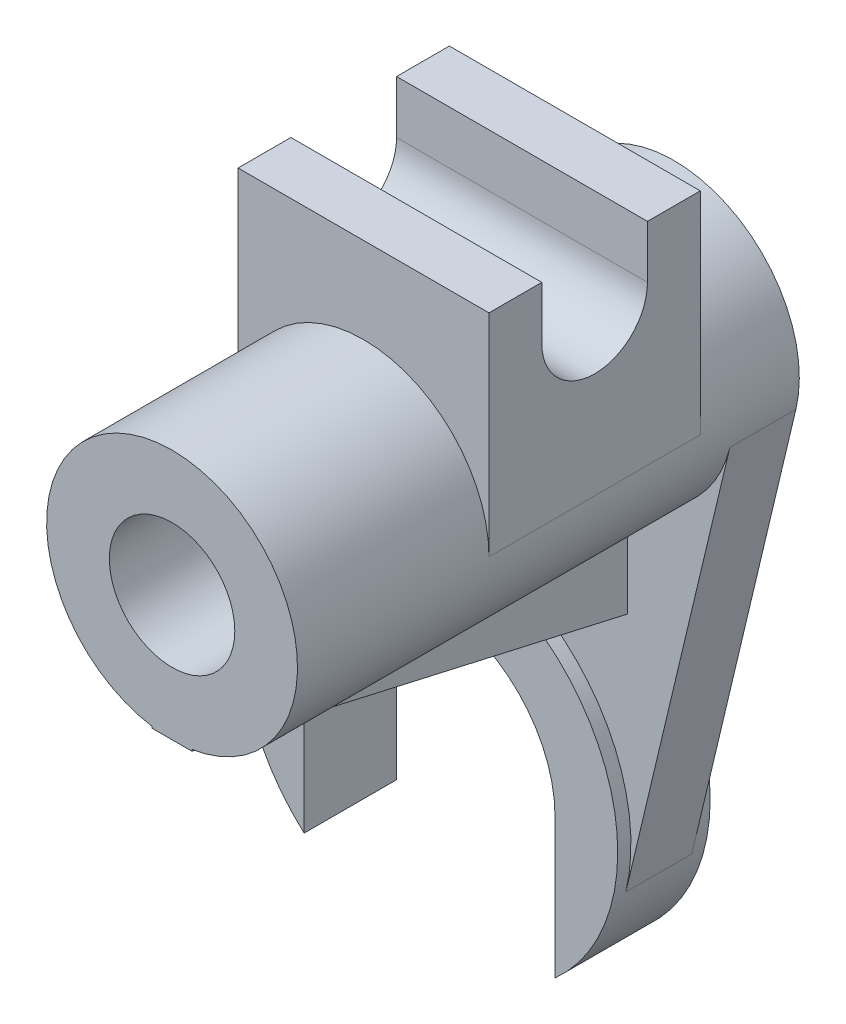
SolidWorks part; units mm, degrees
ref_plane "Front Plane" through (0, 0, 0) normal (0, 0, 1) x (1, 0, 0)
ref_plane "Top Plane" through (0, 0, 0) normal (0, 1, 0) x (1, 0, 0)
ref_plane "Right Plane" through (0, 0, 0) normal (1, 0, 0) x (0, 0, -1)
sketch "Sketch1" plane through (0, 0, 0) normal (0, 0, 1) x (1, 0, 0)
  circle A0 centre (0, 0) radius 19
  dimension "D1" = 38
extrude "Boss-Extrude1" add sketch "Sketch1" along normal mid plane 76
sketch "Sketch2" plane through (0, 0, -38) normal (0, 0, -1) x (-1, 0, 0)
  line L0 (6, -64) -> (6, -85.2426)
  line L1 (44, -64) -> (44, -85.2426)
  arc A0 (44, -64) -> (6, -64) centre (25, -64) ccw
  arc A1 (44, -85.2426) -> (6, -85.2426) centre (25, -64) ccw
  dimension "D1" = 57
  dimension "D3" = 38
  dimension "D2" = 64
  dimension "D4" = 25
extrude "Boss-Extrude2" add sketch "Sketch2" along normal blind 2 and the other way blind 12 separate body
sketch "Sketch3" plane through (0, 0, -38) normal (0, 0, -1) x (-1, 0, 0)
  line L0 (-18.4835, -4.3998) -> (-2.7253, -70.5997)
  line L1 (16.5719, 9.2937) -> (49.8578, -50.0594)
  arc A0 (44, -85.2426) -> (6, -85.2426) centre (25, -64) ccw construction
  circle A1 centre (0, 0) radius 19 construction
  arc A2 (49.8578, -50.0594) -> (-2.7253, -70.5997) centre (25, -64) ccw
  arc A3 (-18.4835, -4.3998) -> (16.5719, 9.2937) centre (0, 0) ccw
extrude "Boss-Extrude3" add sketch "Sketch3" against normal blind 10
sketch "Sketch4" plane through (0, 0, 0) normal (1, 0, 0) x (0, 0, -1)
  line L0 (-9, 0) -> (-9, 32)
  line L1 (-9, 32) -> (-1, 32)
  line L2 (-1, 32) -> (-1, 24)
  line L4 (15, 32) -> (15, 24)
  line L5 (23, 32) -> (15, 32)
  line L6 (23, 0) -> (23, 32)
  line L7 (-9, 0) -> (23, 0)
  line L8 (38, -4.3998) -> (38, 19) construction
  arc A0 (-1, 24) -> (15, 24) centre (7, 24) ccw
  dimension "D2" = 8
  dimension "D1" = 8
  dimension "D3" = 8
  dimension "D5" = 15
  dimension "D6" = 32
  dimension "D7" = 32
extrude "Boss-Extrude4" add sketch "Sketch4" along normal mid plane 38
hole_wizard "Hole1" positions "Sketch6" profile "Sketch7" legacy
sketch "Sketch6" plane through (19, 0, 0) normal (1, 0, 0) x (0, 0, -1)
  point P0 (7, 24)
sketch "Sketch7" plane through (19, 24, -7) normal (0, 1, 0) x (0, 0, -1)
  line L0 (0, 0) -> (0, 100)
  line L1 (0, 100) -> (8, 100)
  line L2 (8, 100) -> (8, 0)
  line L3 (8, 0) -> (0, 0)
  line L4 (0, 110) -> (0, -10) construction
  dimension "Diameter" = 16
  dimension "Depth" = 100
hole_wizard "Hole2" positions "Sketch8" profile "Sketch9" legacy
sketch "Sketch8" plane through (0, 0, 38) normal (0, 0, 1) x (1, 0, 0)
  point P0 (0, 0)
sketch "Sketch9" plane through (0, 0, 38) normal (1, 0, 0) x (0, -1, 0)
  line L0 (0, 0) -> (0, 100)
  line L1 (0, 100) -> (9.5, 100)
  line L2 (9.5, 100) -> (9.5, 0)
  line L3 (9.5, 0) -> (0, 0)
  line L4 (0, 110) -> (0, -10) construction
  dimension "Diameter" = 19
  dimension "Depth" = 100
sketch "Sketch10" plane through (0, 0, 0) normal (1, 0, 0) x (0, 0, -1)
  line L0 (-38, -19) -> (28, -34)
  line L1 (28, -4.3998) -> (28, -70.5997) construction
  line L2 (-38, -19) -> (28, -19) construction
  line L3 (-38, -19) -> (-38, -17)
  line L4 (-38, 19) -> (-38, -19) construction
  line L5 (-38, -17) -> (30, -17)
  line L6 (30, -17) -> (30, -34)
  line L7 (30, -34) -> (28, -34)
  dimension "D1" = 15
  dimension "D2" = 2
  dimension "D3" = 2
extrude "Boss-Extrude5" add sketch "Sketch10" along normal mid plane 6
